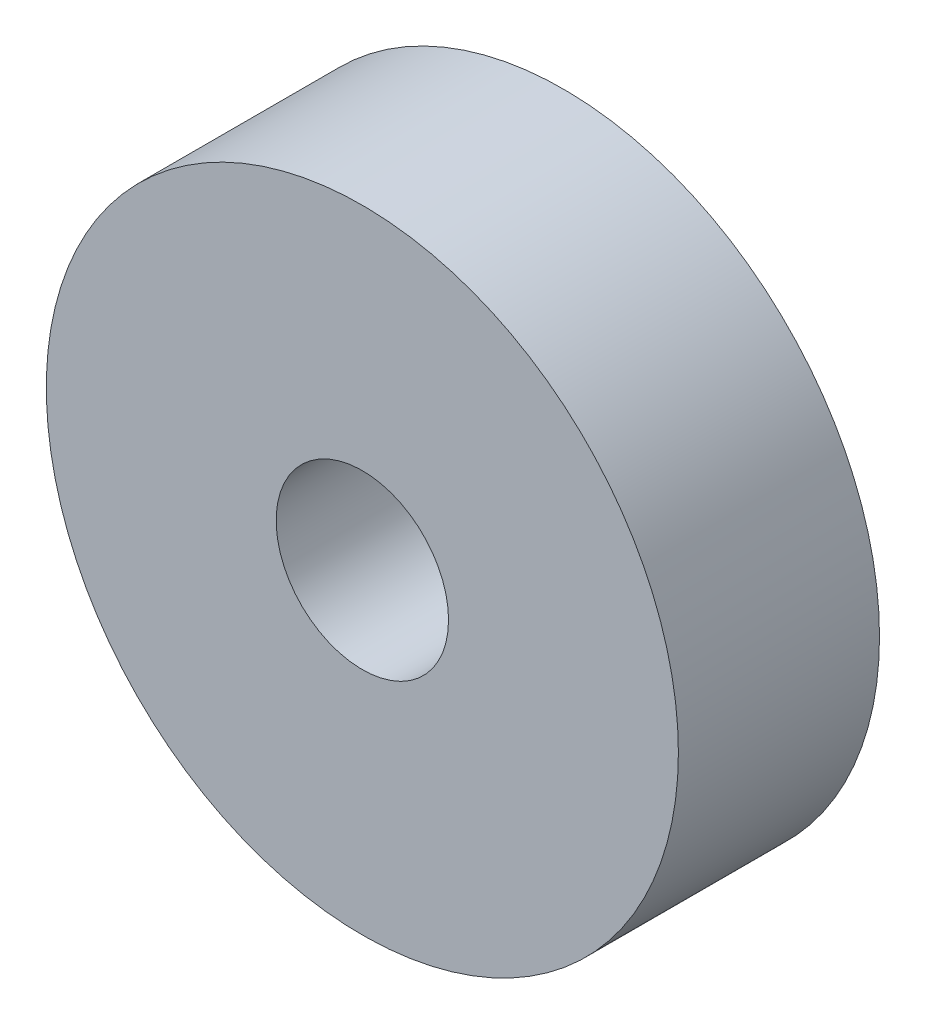
SolidWorks part; units mm, degrees
ref_plane "前视基准面" through (0, 0, 0) normal (0, 0, 1) x (1, 0, 0)
ref_plane "上视基准面" through (0, 0, 0) normal (0, 1, 0) x (1, 0, 0)
ref_plane "右视基准面" through (0, 0, 0) normal (1, 0, 0) x (0, 0, -1)
other "Configuration Table"
sketch "草图1" plane through (0, 0, 0) normal (0, 0, 1) x (1, 0, 0)
  circle A0 centre (0, 0) radius 11
  circle A1 centre (0, 0) radius 3
  dimension "D1" = 6
  dimension "D2" = 22
extrude "凸台-拉伸1" add sketch "草图1" along normal blind 7
